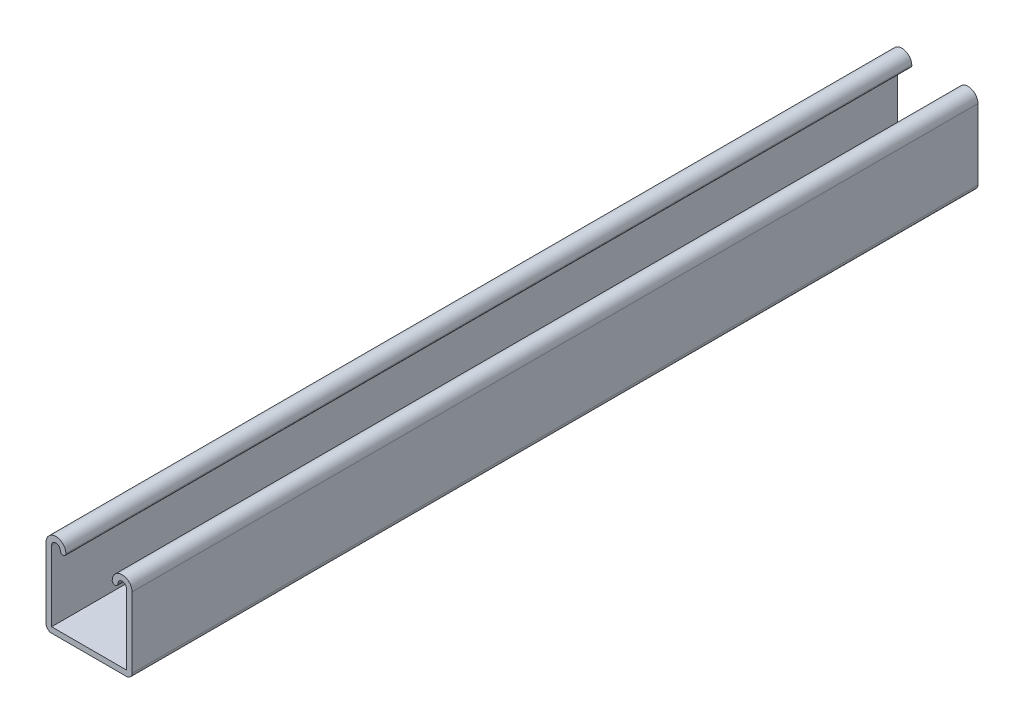
SolidWorks part; units mm, degrees
material "普通碳钢"
ref_plane "前视基准面" through (0, 0, 0) normal (0, 0, 1) x (1, 0, 0)
ref_plane "上视基准面" through (0, 0, 0) normal (0, 1, 0) x (1, 0, 0)
ref_plane "右视基准面" through (0, 0, 0) normal (1, 0, 0) x (0, 0, -1)
sketch "草图1" plane through (0, 0, 0) normal (0, 0, 1) x (1, 0, 0)
  line L0 (0, 0) -> (35.98, 0)
  line L1 (17.99, 2.6924) -> (17.99, -3.3917) construction
  line L2 (35.98, 2.6924) -> (0, 2.6924)
  line L3 (35.98, 19.6088) -> (0, 19.6088) construction
  line L4 (35.98, 2.6924) -> (35.98, 36.5252)
  line L5 (38.6724, 2.6924) -> (38.6724, 36.5252)
  line L6 (-2.6924, 2.6924) -> (-2.6924, 36.5252)
  line L7 (0, 2.6924) -> (0, 36.5252)
  line L8 (17.99, 19.6088) -> (17.99, 2.6924) construction
  arc A0 (35.98, 0) -> (38.6724, 2.6924) centre (35.98, 2.6924) ccw
  arc A1 (35.98, 36.5252) -> (31.8144, 36.5252) centre (33.8972, 36.5252) ccw
  arc A2 (38.6724, 36.5252) -> (29.122, 36.5252) centre (33.8972, 36.5252) ccw
  arc A3 (29.122, 36.5252) -> (31.8144, 36.5252) centre (30.4682, 36.5252) ccw
  arc A4 (6.858, 36.5252) -> (4.1656, 36.5252) centre (5.5118, 36.5252) cw
  arc A5 (-2.6924, 36.5252) -> (6.858, 36.5252) centre (2.0828, 36.5252) cw
  arc A6 (0, 36.5252) -> (4.1656, 36.5252) centre (2.0828, 36.5252) cw
  arc A7 (0, 0) -> (-2.6924, 2.6924) centre (0, 2.6924) cw
  point P25 (17.99, 19.6088)
extrude "凸台-拉伸1" add sketch "草图1" along normal blind 406.4
